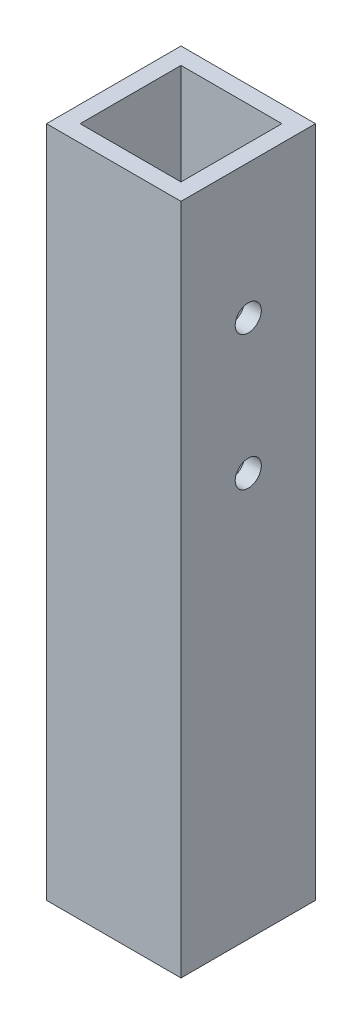
SolidWorks part; units mm, degrees
material "5052-O"
ref_plane "Front Plane" through (0, 0, 0) normal (0, 0, 1) x (1, 0, 0)
ref_plane "Top Plane" through (0, 0, 0) normal (0, 1, 0) x (1, 0, 0)
ref_plane "Right Plane" through (0, 0, 0) normal (1, 0, 0) x (0, 0, -1)
sketch "Sketch1" plane through (0, 0, 0) normal (0, 1, 0) x (1, 0, 0)
  line L0 (-9.525, -9.525) -> (-9.525, 9.525)
  line L1 (-12.7, -12.7) -> (12.7, -12.7)
  line L2 (-12.7, -12.7) -> (-12.7, 12.7)
  line L3 (-12.7, 12.7) -> (12.7, 12.7)
  line L4 (12.7, -12.7) -> (12.7, 12.7)
  line L5 (-12.7, -12.7) -> (12.7, 12.7) construction
  line L6 (-12.7, 12.7) -> (12.7, -12.7) construction
  line L7 (-9.525, 9.525) -> (9.525, 9.525)
  line L8 (9.525, -9.525) -> (9.525, 9.525)
  line L9 (-9.525, -9.525) -> (9.525, -9.525)
  point P0 (0, 0)
  dimension "D1" = 25.4
  dimension "D2" = 25.4
  dimension "D3" = 3.175
extrude "Boss-Extrude1" add sketch "Sketch1" along normal blind 127
sketch "Sketch2" plane through (12.7, 0, 0) normal (1, 0, 0) x (0, 0, -1)
  circle A0 centre (0, 101.6) radius 2.4638
  circle A1 centre (0, 76.2) radius 2.4638
  dimension "D1" = 4.9276
extrude "Cut-Extrude1" cut sketch "Sketch2" against normal through all
